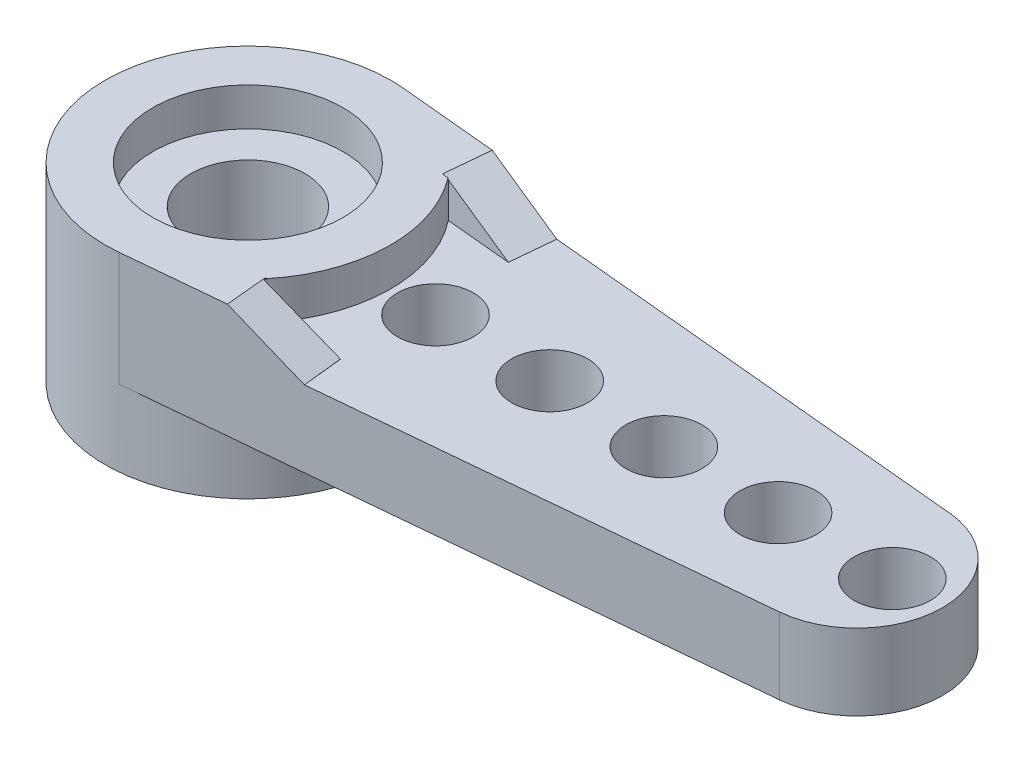
SolidWorks part; units mm, degrees
ref_plane "前视基准面" through (0, 0, 0) normal (0, 0, 1) x (1, 0, 0)
ref_plane "上视基准面" through (0, 0, 0) normal (0, 1, 0) x (1, 0, 0)
ref_plane "右视基准面" through (0, 0, 0) normal (1, 0, 0) x (0, 0, -1)
sketch "草图1" plane through (0, 0, 0) normal (0, 1, 0) x (1, 0, 0)
  line L0 (0.3516, 3.7335) -> (16.2109, 2.2401)
  line L1 (0.3516, -3.7335) -> (16.2109, -2.2401)
  circle A0 centre (0, 0) radius 3.75
  circle A1 centre (16, 0) radius 2.25
  point P9 (0, 0)
  dimension "D1" = 7.5
  dimension "D2" = 4.5
  dimension "D3" = 16
extrude "凸台-拉伸1" add sketch "草图1" along normal blind 2 contours A0 | A1 L0 A0 L1 | A1
sketch "草图2" plane through (0, 2, 0) normal (0, 1, 0) x (1, 0, 0)
  circle A0 centre (0, 0) radius 3.75
  circle A1 centre (0, 0) radius 2.5
  dimension "D1" = 5
extrude "凸台-拉伸2" add sketch "草图2" along normal blind 1
sketch "草图3" plane through (0, 0, 0) normal (0, -1, 0) x (1, 0, 0)
  circle A0 centre (0, 0) radius 3.75
  circle A1 centre (0, 0) radius 2.5
  dimension "D1" = 5
extrude "凸台-拉伸3" add sketch "草图3" along normal blind 2
sketch "草图4" plane through (0, 2, 0) normal (0, 1, 0) x (1, 0, 0)
  line L0 (0, 0) -> (50000, 0) construction
  circle A0 centre (0, 0) radius 1.5
  circle A1 centre (4.9275, 0) radius 1
  circle A2 centre (7.9275, 0) radius 1
  circle A3 centre (10.9275, 0) radius 1
  circle A4 centre (13.9275, 0) radius 1
  circle A5 centre (16.9275, 0) radius 1
  dimension "D1" = 3
  dimension "D2" = 2
  dimension "D3" = 3
  dimension "D4" = 3
  dimension "D5" = 3
  dimension "D6" = 3
extrude "切除-拉伸1" cut sketch "草图4" against normal blind 2
sketch "草图5" plane through (0, 2, 0) normal (0, 1, 0) x (1, 0, 0)
  line L0 (0.3516, 3.7335) -> (4.7992, 3.3147)
  line L1 (0.3516, 3.7335) -> (16.2109, 2.2401) construction
  line L2 (4.7992, 3.3147) -> (4.6897, 2.1513)
  line L3 (4.6897, 2.1513) -> (2.9501, 2.3151)
  line L4 (0.3516, -3.7335) -> (4.7992, -3.3147)
  line L5 (0.3516, -3.7335) -> (16.2109, -2.2401) construction
  line L6 (4.7992, -3.3147) -> (4.6897, -2.2588)
  line L7 (4.6897, -2.2588) -> (2.8382, -2.4509)
  arc A0 (0.3516, -3.7335) -> (0.3516, 3.7335) centre (0, 0) ccw construction
  arc A1 (2.9501, 2.3151) -> (0.3516, 3.7335) centre (0, 0) ccw
  arc A2 (2.8382, -2.4509) -> (0.3516, -3.7335) centre (0, 0) cw
extrude "凸台-拉伸4" add sketch "草图5" along normal blind 1
sketch "草图6" plane through (0.3516, 0, 3.7335) normal (0.0937, 0, 0.9956) x (0.9956, 0, -0.0937)
  line L0 (2.6103, 3) -> (4.4673, 2)
  line L1 (0, 3) -> (4.4673, 3) construction
  line L2 (4.4673, 2) -> (4.4673, 3)
  line L3 (4.4673, 3) -> (2.6103, 3)
extrude "切除-拉伸2" cut sketch "草图6" against normal blind 1.1
sketch "草图7" plane through (0.3516, 0, -3.7335) normal (0.0938, 0, -0.9956) x (-0.9956, 0, -0.0938)
  line L0 (-2.5864, 3) -> (-4.4673, 2)
  line L1 (-4.4673, 3) -> (0, 3) construction
  line L4 (-4.4673, 2) -> (-4.4673, 3)
  line L5 (-4.4673, 3) -> (-2.5864, 3)
extrude "切除-拉伸4" cut sketch "草图7" against normal blind 1.2
